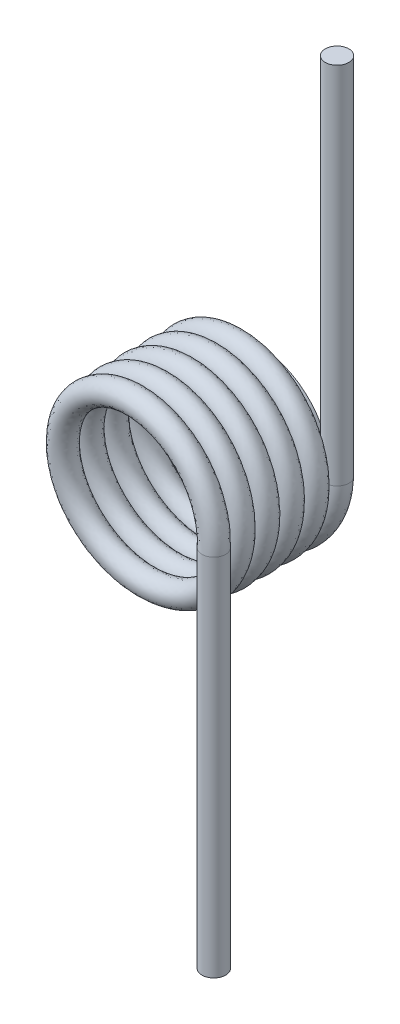
SolidWorks part; units mm, degrees
ref_plane "Спереди" through (0, 0, 0) normal (0, 0, 1) x (1, 0, 0)
ref_plane "Сверху" through (0, 0, 0) normal (0, 1, 0) x (1, 0, 0)
ref_plane "Справа" through (0, 0, 0) normal (1, 0, 0) x (0, 0, -1)
sketch "Эскиз1" plane through (0, 0, 0) normal (0, 0, 1) x (1, 0, 0)
  circle A0 centre (0, 0) radius 2.35
curve "Спираль1" pitch 0.71 height 3.55 turns 5
sketch "Эскиз6" plane through (0, 0, 0) normal (0, 1, 0) x (1, 0, 0)
  circle A0 centre (2.35, 0) radius 0.34
  spline S0 degree 3 poles (2.35, 0) (2.35, -0.0147) (2.2276, -0.0444) (1.705, -0.0887) (0.9227, -0.1331) (0, -0.1775) (-0.9227, -0.2219) (-1.705, -0.2662) (-2.2276, -0.3106) (-2.4112, -0.355) (-2.2276, -0.3994) (-1.705, -0.4437) (-0.9227, -0.4881) (0, -0.5325) (0.9227, -0.5769) (1.705, -0.6212) (2.2276, -0.6656) (2.4112, -0.71) (2.2276, -0.7544) (1.705, -0.7987) (0.9227, -0.8431) (0, -0.8875) (-0.9227, -0.9319) (-1.705, -0.9763) (-2.2276, -1.0206) (-2.4112, -1.065) (-2.2276, -1.1094) (-1.705, -1.1538) (-0.9227, -1.1981) (0, -1.2425) (0.9227, -1.2869) (1.705, -1.3313) (2.2276, -1.3756) (2.4112, -1.42) (2.2276, -1.4644) (1.705, -1.5087) (0.9227, -1.5531) (0, -1.5975) (-0.9227, -1.6419) (-1.705, -1.6862) (-2.2276, -1.7306) (-2.4112, -1.775) (-2.2276, -1.8194) (-1.705, -1.8637) (-0.9227, -1.9081) (0, -1.9525) (0.9227, -1.9969) (1.705, -2.0412) (2.2276, -2.0856) (2.4112, -2.13) (2.2276, -2.1744) (1.705, -2.2187) (0.9227, -2.2631) (0, -2.3075) (-0.9227, -2.3519) (-1.705, -2.3962) (-2.2276, -2.4406) (-2.4112, -2.485) (-2.2276, -2.5294) (-1.705, -2.5738) (-0.9227, -2.6181) (0, -2.6625) (0.9227, -2.7069) (1.705, -2.7513) (2.2276, -2.7956) (2.4112, -2.84) (2.2276, -2.8844) (1.705, -2.9288) (0.9227, -2.9731) (0, -3.0175) (-0.9227, -3.0619) (-1.705, -3.1063) (-2.2276, -3.1506) (-2.4112, -3.195) (-2.2276, -3.2394) (-1.705, -3.2838) (-0.9227, -3.3281) (0, -3.3725) (0.9227, -3.4169) (1.705, -3.4613) (2.2276, -3.5056) (2.35, -3.5353) (2.35, -3.55) knots 0 0 0 0 0.0125 0.025 0.0375 0.05 0.0625 0.075 0.0875 0.1 0.1125 0.125 0.1375 0.15 0.1625 0.175 0.1875 0.2 0.2125 0.225 0.2375 0.25 0.2625 0.275 0.2875 0.3 0.3125 0.325 0.3375 0.35 0.3625 0.375 0.3875 0.4 0.4125 0.425 0.4375 0.45 0.4625 0.475 0.4875 0.5 0.5125 0.525 0.5375 0.55 0.5625 0.575 0.5875 0.6 0.6125 0.625 0.6375 0.65 0.6625 0.675 0.6875 0.7 0.7125 0.725 0.7375 0.75 0.7625 0.775 0.7875 0.8 0.8125 0.825 0.8375 0.85 0.8625 0.875 0.8875 0.9 0.9125 0.925 0.9375 0.95 0.9625 0.975 0.9875 1 1 1 1 construction
sweep "По траектории9" add profiles "Эскиз6" path "Спираль1"
sketch "Эскиз7" plane through (0, 0, 0) normal (0, -1, 0) x (1, 0, 0)
  circle A0 centre (2.35, 3.55) radius 0.34
extrude "Вытянуть1" add sketch "Эскиз7" along normal blind 10.5
sketch "Эскиз8" plane through (0, 0, 0) normal (0, 1, 0) x (1, 0, 0)
  circle A0 centre (2.35, 0) radius 0.34
extrude "Вытянуть2" add sketch "Эскиз8" along normal blind 10.5
sketch "Эскиз9" plane through (0, 0, 0) normal (0, 0, 1) x (1, 0, 0)
  circle A0 centre (0, 0) radius 2
sketch "Эскиз12" plane through (0, 0, 0) normal (0, 1, 0) x (1, 0, 0)
  line L2 (-2.0693, 0.0721) -> (-1.9307, 0.0721)
  line L3 (-2.0693, 0.0721) -> (-2.0693, -0.0721)
  line L4 (-2.0693, -0.0721) -> (-1.9307, -0.0721)
  line L5 (-1.9307, 0.0721) -> (-1.9307, -0.0721)
  line L6 (-2.0693, 0.0721) -> (-1.9307, -0.0721) construction
  line L7 (-2.0693, -0.0721) -> (-1.9307, 0.0721) construction
sweep "По траектории12" add profiles "Эскиз12" path "Эскиз9"
